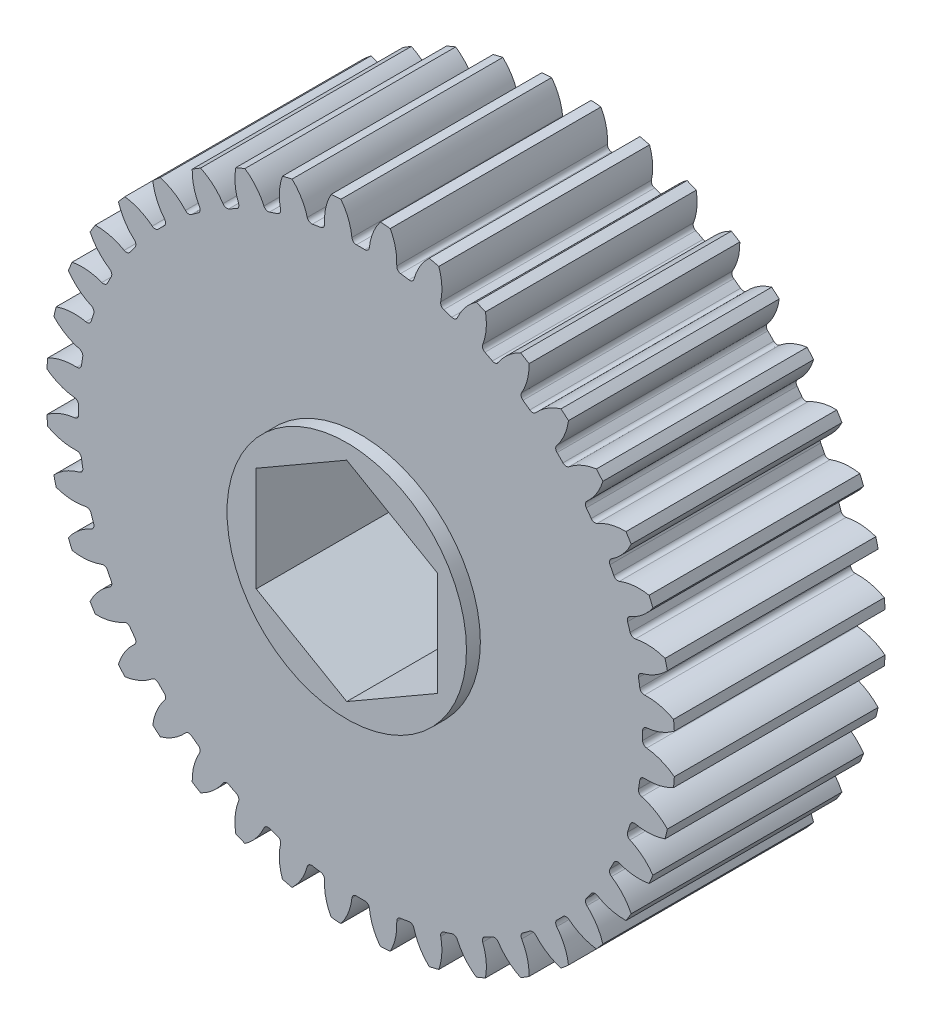
SolidWorks part; units mm, degrees
material "7075-T6 (SN)"
ref_plane "Alzado" through (0, 0, 0) normal (0, 0, 1) x (1, 0, 0)
ref_plane "Planta" through (0, 0, 0) normal (0, 1, 0) x (1, 0, 0)
ref_plane "Vista lateral" through (0, 0, 0) normal (1, 0, 0) x (0, 0, -1)
sketch "Croquis1" plane through (0, 0, 0) normal (0, 0, 1) x (1, 0, 0)
  circle A0 centre (0, 0) radius 15.875 construction
  circle A1 centre (0, 0) radius 16.6687
  dimension "D" = 31.75
  dimension "OD" = 33.3375
extrude "Saliente-Extruir1" add sketch "Croquis1" along normal mid plane 11.176
sketch "Croquis2" plane through (0, 0, 0) normal (0, 0, 1) x (1, 0, 0)
  line L0 (0, 0) -> (0, 16.6687) construction
  line L1 (0, 0) -> (2.6076, 16.4635) construction
  line L2 (0, 0) -> (1.3078, 16.6174) construction
  line L3 (-0.4481, 14.9499) -> (0, 0) construction
  line L4 (-0.6232, 15.8628) -> (0.6232, 15.8628) construction
  line L5 (0.6232, 15.8628) -> (1.8659, 15.765) construction
  line L6 (-0.9076, 16.644) -> (0, 14.1504) construction
  circle A0 centre (0, 0) radius 16.6687 construction
  arc A2 (0.4481, 14.9499) -> (-0.4481, 14.9499) centre (0, 0) ccw
  circle A5 centre (0, 0) radius 15.875 construction
  arc A6 (-1.0459, 16.6359) -> (-0.4481, 14.9499) centre (-3.3721, 14.8623) cw
  arc A7 (1.0459, 16.6359) -> (0.4481, 14.9499) centre (3.3721, 14.8623) ccw
  arc A8 (1.0459, 16.6359) -> (-1.0459, 16.6359) centre (0, 0) ccw
  dimension "D1" = 9
  dimension "D2" = 4.5
  dimension "B" = 0.9184
  dimension "Pressure Angle" = 20
extrude "Cortar-Extruir1" cut sketch "Croquis2" against normal through all both and the other way through all
fillet "Redondeo1" radius 0.2381 2 edges at (0.4481, 14.9499, 0) (-0.4481, 14.9499, 0)
pattern_circular "MatrizC1" count 40 over 360 about axis through (0, 0, 0) along (0, 0, 1) of "Cortar-Extruir1", "Redondeo1"
sketch "Croquis3" plane through (0, 0, 0) normal (0, 0, 1) x (1, 0, 0)
  circle A0 centre (0, 0) radius 6.35
  dimension "sp" = 12.7
extrude "Saliente-Extruir2" add sketch "Croquis3" along normal mid plane 12.6492
sketch "Croquis4" plane through (0, 0, 0) normal (0, 0, 1) x (1, 0, 0)
  line L1 (0, 5.5433) -> (-4.8006, 2.7716)
  line L2 (-4.8006, 2.7716) -> (-4.8006, -2.7716)
  line L3 (-4.8006, -2.7716) -> (0, -5.5433)
  line L4 (0, -5.5433) -> (4.8006, -2.7716)
  line L5 (4.8006, -2.7716) -> (4.8006, 2.7716)
  line L6 (4.8006, 2.7716) -> (0, 5.5433)
  circle A0 centre (0, 0) radius 4.8006 construction
  dimension "D1" = 9.6012
extrude "Cortar-Extruir2" cut sketch "Croquis4" against normal through all both and the other way through all
sketch "Croquis5" [suppressed] plane through (0, 0, 5.588) normal (0, 0, 1) x (1, 0, 0)
  circle A0 centre (0, 0) radius 7.9375
  circle A1 centre (0, 0) radius 36.2931
  circle A2 centre (0, 0) radius 40.4813 construction
  dimension "D1" = 15.875
  dimension "D2" = 4.1881
extrude "Cortar-Extruir3" [suppressed] cut sketch "Croquis5" against normal blind 4.3
fillet "Redondeo2" [suppressed] radius 3
mirror "Simetría1" [suppressed] about plane through (0, 0, 0) normal (0, 0, 1)
equation "\"Number of teeth\" = 40"
equation "\"Diametral Pitch\"= 32"
equation "\"Pressure Angle\"= 20"
equation "\"D@Croquis1\"=\"Number of teeth\"/\"Diametral Pitch\""
equation "\"OD@Croquis1\"=(\"Number of teeth\"+2) /\"Diametral Pitch\""
equation "\"D2@Croquis2\"=(360 / \"Number of teeth\")/ 2."
equation "\"D1@Croquis2\"=360 / \"Number of teeth\""
equation "\"B@Croquis2\"=1.157 / \"Diametral Pitch\""
equation "\"Pressure Angle@Croquis2\" = \"Pressure Angle\""
equation "\"D1@Redondeo1\"=(pi / \"Diametral Pitch\") * .0955"
equation "\"D1@MatrizC1\"=\"Number of teeth\""
